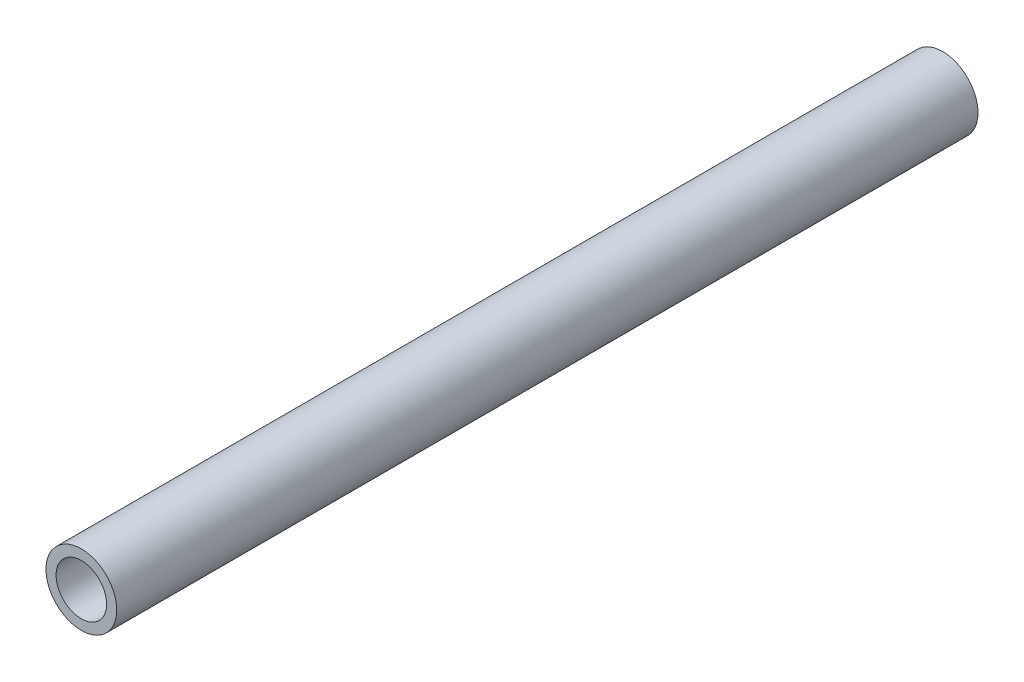
SolidWorks part; units mm, degrees
material "1.0553 (S355J0)"
ref_plane "Front Plane" through (0, 0, 0) normal (0, 0, 1) x (1, 0, 0)
ref_plane "Top Plane" through (0, 0, 0) normal (0, 1, 0) x (1, 0, 0)
ref_plane "Right Plane" through (0, 0, 0) normal (1, 0, 0) x (0, 0, -1)
sketch "Sketch1" plane through (0, 0, 0) normal (1, 0, 0) x (0, 0, -1)
  line L0 (0, 50) -> (0, 70)
  line L1 (0, 70) -> (-1705, 70)
  line L2 (-1705, 70) -> (-1705, 50)
  line L3 (-1705, 50) -> (0, 50)
  line L4 (30.0522, 0) -> (-755.8122, 0) construction
  line L5 (0, 0) -> (0, 50) construction
  dimension "D1" = 100
  dimension "D2" = 140
  dimension "D3" = 1705
revolve "Revolve1" add sketch "Sketch1" angle 360 about L4
